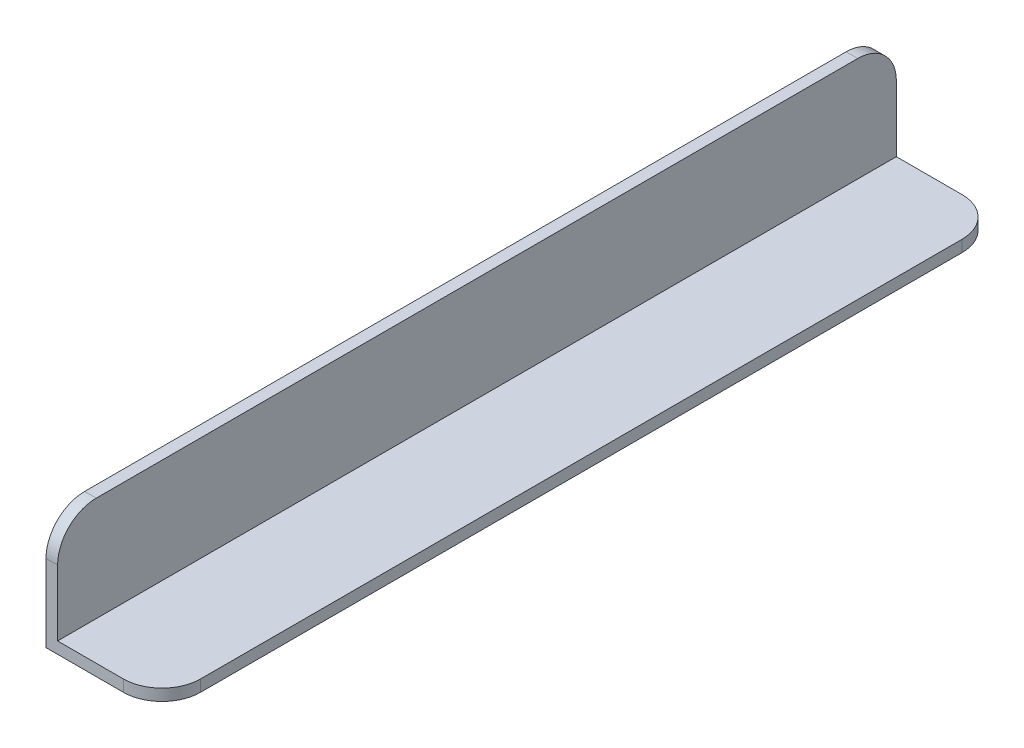
SolidWorks part; units mm, degrees
material "AISI 304"
ref_plane "Спереди" through (0, 0, 0) normal (0, 0, 1) x (1, 0, 0)
ref_plane "Сверху" through (0, 0, 0) normal (0, 1, 0) x (1, 0, 0)
ref_plane "Справа" through (0, 0, 0) normal (1, 0, 0) x (0, 0, -1)
sketch "Эскиз1" plane through (0, 0, 0) normal (0, 0, 1) x (1, 0, 0)
  line L0 (0, 0) -> (60, 0)
  line L1 (60, 0) -> (60, 6)
  line L2 (60, 6) -> (6, 6)
  line L3 (6, 6) -> (6, 60)
  line L4 (6, 60) -> (0, 60)
  line L5 (0, 60) -> (0, 0)
  dimension "D1" = 60
  dimension "D2" = 6
extrude "Бобышка-Вытянуть1" add sketch "Эскиз1" along normal mid plane 434
fillet "Скругление1" radius 20 4 edges at (3, 60, -217) (60, 3, -217) (3, 60, 217) (60, 3, 217)
sketch "Эскиз3" plane through (6, 0, 0) normal (1, 0, 0) x (0, 0, -1)
  line L0 (-197, 60) -> (197, 60) construction
  line L1 (-217, 6) -> (-217, 40) construction
  line L2 (0, 33) -> (0, -33) construction
  circle A0 centre (-182, 38) radius 12.5
  circle A1 centre (182, 38) radius 12.5
  dimension "D1" = 22
  dimension "D2" = 35
  dimension "D3" = 25
extrude "Вырез-Вытянуть2" [suppressed] cut sketch "Эскиз3" against normal through all both
